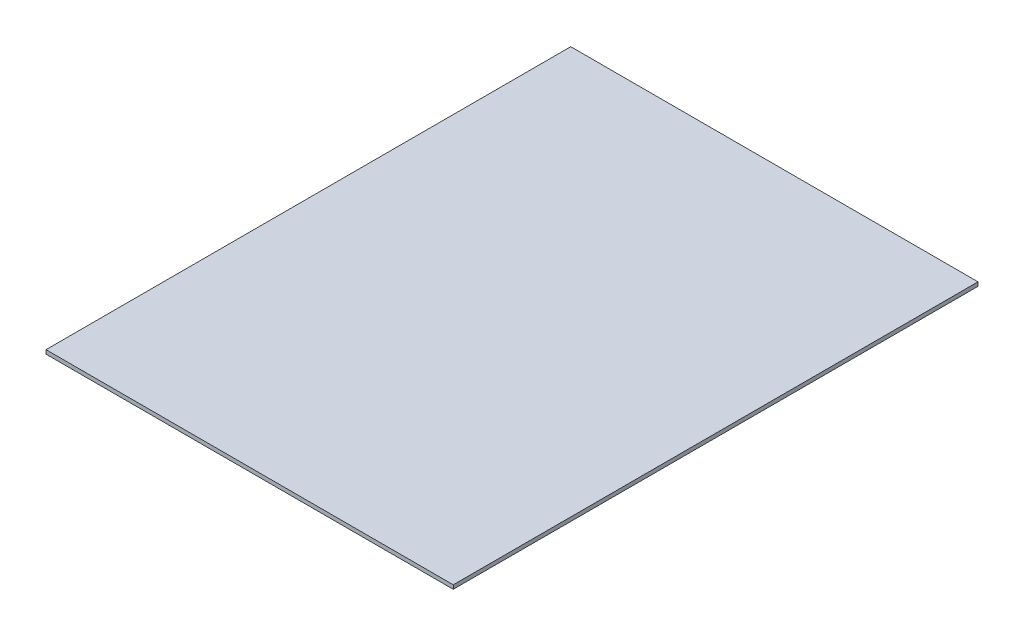
SolidWorks part; units mm, degrees
ref_plane "前视基准面" through (0, 0, 0) normal (0, 0, 1) x (1, 0, 0)
ref_plane "上视基准面" through (0, 0, 0) normal (0, 1, 0) x (1, 0, 0)
ref_plane "右视基准面" through (0, 0, 0) normal (1, 0, 0) x (0, 0, -1)
sketch "草图1" plane through (0, 0, 0) normal (0, 1, 0) x (1, 0, 0)
  line L1 (-260, 335) -> (260, 335)
  line L2 (-260, 335) -> (-260, -335)
  line L3 (-260, -335) -> (260, -335)
  line L4 (260, 335) -> (260, -335)
  line L5 (-260, 335) -> (260, -335) construction
  line L6 (-260, -335) -> (260, 335) construction
  point P0 (0, 0)
  dimension "D1" = 670
  dimension "D2" = 520
extrude "凸台-拉伸1" add sketch "草图1" along normal blind 5
